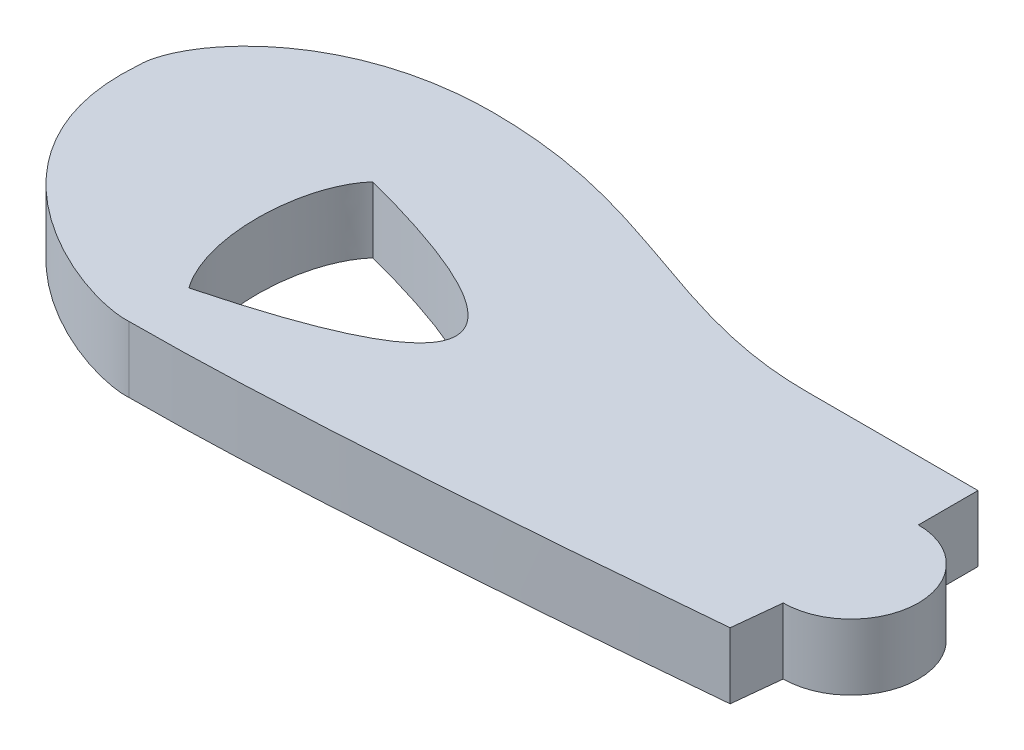
SolidWorks part; units mm, degrees
ref_plane "Front Plane" through (0, 0, 0) normal (0, 0, 1) x (1, 0, 0)
ref_plane "Top Plane" through (0, 0, 0) normal (0, 1, 0) x (1, 0, 0)
ref_plane "Right Plane" through (0, 0, 0) normal (1, 0, 0) x (0, 0, -1)
sketch "Sketch1" plane through (0, 0, 0) normal (0, 1, 0) x (1, 0, 0)
  line L0 (0, 0) -> (29.8, 0) construction
  line L1 (0, 0) -> (0, 24.3) construction
  line L2 (0, 0) -> (0, -22.5) construction
  line L3 (0, 0) -> (-86.5, 0) construction
  line L4 (-26, 0) -> (-26, 24.3) construction
  line L5 (-86.5, 0) -> (-86.5, 37.2) construction
  line L6 (-86.5, 11.6) -> (-124.6, 11.6) construction
  line L7 (-86.5, 0) -> (-86.5, -27.9) construction
  dimension "D1" = 29.8
  dimension "D2" = 24.3
  dimension "D3" = 22.5
  dimension "D4" = 26
  dimension "D5" = 86.5
  dimension "D6" = 27.9
  dimension "D7" = 37.2
  dimension "D8" = 11.6
  dimension "D9" = 38.1
sketch "Sketch2" plane through (0, 0, 0) normal (0, 1, 0) x (1, 0, 0)
  line L0 (-26, 24.3) -> (0, 24.3)
  line L1 (-124.6, 0.1449) -> (-124.6, 23.0551) construction
  line L2 (-106.5667, 37.2) -> (-66.4333, 37.2) construction
  line L3 (-42.2984, 24.3) -> (-9.7006, 24.3) construction
  line L4 (-107.4998, 37.2) -> (-65.4572, 37.2) construction
  line L5 (-64.2941, -27.9) -> (-108.7059, -27.9) construction
  line L6 (29.8, -11.2792) -> (29.8, 11.2792) construction
  line L7 (29.8, -14.0147) -> (29.8, 14.0918) construction
  spline S0 degree 3 poles (-26, 24.3) (-46.3736, 24.3) (-60.2234, 37.2) (-86.5, 37.2) knots 0 0 0 0 1 1 1 1
  spline S1 degree 3 poles (-86.5, 37.2) (-111.5833, 37.2) (-124.6, 21.1459) (-124.6, 11.6) knots 0 0 0 0 1 1 1 1
  spline S2 degree 3 poles (0, 24.3) (20.6838, 24.3847) (29.8, 14.099) (29.8, 0) knots 0 0 0 0 1 1 1 1
  spline S3 degree 3 poles (29.8, 0) (29.8, -15.9034) (12.7938, -19.6737) (0, -22.5) knots 0 0 0 0 1 1 1 1
  spline S4 degree 2 poles (-86.5, -27.9) (-58.7426, -27.9) (0, -22.5) knots 0 0 0 1 1 1
  spline S5 degree 3 poles (-124.6, 11.6) (-126.6455, -15.9296) (-96.1692, -28.4589) (-86.5, -27.9) knots 0 0 0 0 1 1 1 1
  point P0 (0, 24.3)
  point P2 (29.8, 0)
  point P4 (0, -22.5)
  point P6 (-26, 24.3)
  point P8 (-86.5, 37.2)
  point P10 (-124.6, 11.6)
  point P12 (-86.5, -27.9)
extrude "Boss-Extrude1" add sketch "Sketch2" along normal blind 10
sketch "Sketch5" plane through (0, 10, 0) normal (0, 1, 0) x (1, 0, 0)
  line L2 (0, 19.3) -> (-26, 19.3)
  line L3 (0, 19.3) -> (-26, 19.3)
  line L4 (-133.1401, 55.1699) -> (57.5258, 55.1699)
  line L5 (-133.1401, 55.1699) -> (-133.1401, -43.745)
  line L6 (-133.1401, -43.745) -> (57.5258, -43.745)
  line L7 (57.5258, 55.1699) -> (57.5258, -43.745)
  spline S10 degree 3 poles (794.3178, 2896.6346) (236.5633, 295.2684) (75.1344, 4.3942) (-36.2999, 20.219) (-38.8232, 20.7499) (-43.8284, 22.0533) (-46.3131, 22.8262) (-51.2444, 24.4704) (-53.694, 25.3411) (-58.6071, 27.0407) (-61.0707, 27.8688) (-64.8063, 28.9893) (-66.0595, 29.343) (-68.5722, 29.9962) (-69.8324, 30.2958) (-73.6263, 31.1023) (-76.1734, 31.5152) (-394.4154, 65.5197) (-1008.6606, -1988.9699) (-1423.0021, -2645.3199) knots -5.207716 -5.207716 -5.207716 -5.207716 0.125 0.125 0.25 0.25 0.375 0.375 0.5 0.5 0.625 0.625 0.6875 0.6875 0.75 0.75 0.875 0.875 16.247306 16.247306 16.247306 16.247306 only from (-26, 19.3) to (-86.5, 32.2)
  spline S11 degree 3 poles (-155.0275, 3009.7498) (283.9644, -579.3508) (39.2092, 61.7589) (-97.8181, 30.8894) (-98.6695, 30.6698) (-100.363, 30.1729) (-101.2079, 29.8946) (-103.7072, 28.973) (-105.3145, 28.249) (-108.4025, 26.5648) (-109.8852, 25.604) (-112.6954, 23.4124) (-113.9894, 22.2093) (-115.7364, 20.2177) (-116.2861, 19.5225) (-117.3076, 18.0567) (-117.7719, 17.2971) (-118.3806, 16.1123) (-118.5688, 15.7095) (-118.9104, 14.8853) (-119.0639, 14.463) (-119.321, 13.6124) (-119.4258, 13.1825) (-119.5345, 12.528) (-119.5626, 12.3083) (-119.5889, 11.9755) (-119.595, 11.8641) (-119.8529, 2.1663) (-91.4737, -13.0524) (-3067.996, 562.8701) knots -9.69525 -9.69525 -9.69525 -9.69525 0.25 0.25 0.3125 0.3125 0.375 0.375 0.5 0.5 0.625 0.625 0.75 0.75 0.8125 0.8125 0.875 0.875 0.90625 0.90625 0.9375 0.9375 0.96875 0.96875 0.984375 0.984375 0.992188 0.992188 1.660503 1.660503 1.660503 1.660503 only from (-86.5, 32.2) to (-119.6, 11.4145)
  spline S12 degree 3 poles (-3114.144, -159.344) (-75.3215, 65.211) (-118.2824, 36.1888) (-119.6695, 10.3135) (-119.7026, 9.4894) (-119.7017, 8.668) (-119.6533, 7.0291) (-119.5587, 5.9417) (-119.3168, 4.3187) (-119.2195, 3.7791) (-118.9903, 2.7027) (-118.8578, 2.164) (-118.4114, 0.5683) (-118.0496, -0.4661) (-117.2048, -2.4791) (-116.7219, -3.4578) (-115.911, -4.8862) (-115.6263, -5.3557) (-115.0287, -6.2817) (-114.7151, -6.739) (-113.0981, -8.9672) (-111.6366, -10.5868) (-109.2434, -12.8211) (-108.4118, -13.5331) (-107.1168, -14.5549) (-106.6765, -14.8883) (-105.787, -15.5353) (-105.3374, -15.8493) (-103.0661, -17.3743) (-101.1758, -18.4523) (-98.2376, -19.8702) (-97.2408, -20.3092) (-95.21, -21.1148) (-94.1746, -21.4822) (-92.0643, -22.1268) (-91.001, -22.402) (-89.3879, -22.7093) (-88.8471, -22.7942) (-88.0288, -22.8795) (-87.7547, -22.9009) (-87.3409, -22.9165) (-87.2025, -22.919) (-75.8543, -22.7912) (-57.6729, 17.6935) (-565.1077, -2984.244) knots -1.438804 -1.438804 -1.438804 -1.438804 0.015625 0.015625 0.03125 0.0625 0.0625 0.125 0.125 0.15625 0.15625 0.1875 0.1875 0.25 0.25 0.3125 0.3125 0.34375 0.34375 0.375 0.375 0.5 0.5 0.5625 0.5625 0.59375 0.59375 0.625 0.625 0.75 0.75 0.8125 0.8125 0.875 0.875 0.9375 0.9375 0.96875 0.96875 0.984375 0.984375 0.992187 0.992187 1.621629 1.621629 1.621629 1.621629 only from (-119.6, 11.4145) to (-86.6438, -22.9)
  spline S13 degree 3 poles (-743.0619, 2883.7324) (-404.1471, 44.7095) (-237.6226, -27.3739) (-72.2929, -22.6309) (-68.7098, -22.4892) (-57.9653, -21.9864) (-50.8087, -21.5494) (-36.5025, -20.5633) (-29.353, -20.0121) (442.1069, 18.8609) (896.2577, 220.25) (1524.6058, -2374.3013) knots -5.513822 -5.513822 -5.513822 -5.513822 0.125 0.125 0.25 0.25 0.5 0.5 0.75 0.75 16.991268 16.991268 16.991268 16.991268 only from (-86.6438, -22.9) to (-0.7711, -17.5498)
  spline S14 degree 3 poles (684.9632, -2932.2413) (-188.4077, 55.2091) (-72.0811, -37.5503) (8.73, -15.2186) (10.0645, -14.8145) (12.6997, -13.9014) (14.0008, -13.3934) (15.9119, -12.5052) (16.5421, -12.1879) (17.7844, -11.497) (18.3919, -11.1257) (19.5594, -10.3246) (20.1212, -9.8941) (20.9205, -9.1892) (21.1807, -8.9434) (21.6785, -8.4347) (21.9161, -8.1719) (22.5926, -7.3563) (22.9947, -6.7761) (23.5131, -5.8423) (23.6718, -5.5198) (23.9536, -4.8681) (24.0777, -4.5373) (24.4029, -3.5305) (24.5567, -2.8403) (31.3062, 45.0348) (-209.6675, 121.1409) (2725.17, -1306.3496) knots -7.13592 -7.13592 -7.13592 -7.13592 0.25 0.25 0.375 0.375 0.5 0.5 0.5625 0.5625 0.625 0.625 0.6875 0.6875 0.71875 0.71875 0.75 0.75 0.8125 0.8125 0.84375 0.84375 0.875 0.875 0.9375 0.9375 5.110249 5.110249 5.110249 5.110249 only from (-0.7711, -17.5498) to (24.8, 0)
  spline S15 degree 3 poles (3003.4514, 307.3213) (-329.5265, -207.9997) (38.0399, -68.0338) (24.2703, 5.1555) (24.0952, 5.8744) (23.7648, 6.9407) (23.6433, 7.2941) (23.3755, 7.9966) (23.2292, 8.3451) (22.7584, 9.3658) (22.3999, 10.019) (21.5892, 11.2682) (21.1362, 11.865) (19.6347, 13.56) (18.4892, 14.5137) (16.9097, 15.5257) (16.5854, 15.7195) (15.9298, 16.0859) (15.5982, 16.2589) (14.5926, 16.7499) (13.9081, 17.0401) (12.5153, 17.5579) (11.807, 17.7854) (10.3698, 18.1863) (9.6387, 18.36) (7.4366, 18.806) (5.959, 19.0045) (-85.4866, 26.721) (-201.9485, -238.1682) (23.3888, 3011.2925) knots -6.115667 -6.115667 -6.115667 -6.115667 0.125 0.125 0.1875 0.1875 0.21875 0.21875 0.25 0.25 0.3125 0.3125 0.375 0.375 0.5 0.5 0.53125 0.53125 0.5625 0.5625 0.625 0.625 0.6875 0.6875 0.75 0.75 0.875 0.875 8.448739 8.448739 8.448739 8.448739 only from (24.8, 0) to (0, 19.3)
  spline S16 degree 3 poles (-26, 19.3) (-28.6144, 19.3) (-31.1955, 19.4941) (-36.2999, 20.219) (-38.8232, 20.7499) (-43.8284, 22.0533) (-46.3131, 22.8262) (-51.2444, 24.4704) (-53.694, 25.3411) (-58.6071, 27.0407) (-61.0707, 27.8688) (-64.8063, 28.9893) (-66.0595, 29.343) (-68.5722, 29.9962) (-69.8324, 30.2958) (-73.6263, 31.1023) (-76.1734, 31.5152) (-81.3072, 32.0638) (-83.8939, 32.2) (-86.5, 32.2) knots 0 0 0 0 0.125 0.125 0.25 0.25 0.375 0.375 0.5 0.5 0.625 0.625 0.6875 0.6875 0.75 0.75 0.875 0.875 1 1 1 1
  spline S17 degree 3 poles (-86.5, 32.2) (-90.0477, 32.2) (-93.5393, 31.8534) (-97.8181, 30.8894) (-98.6695, 30.6698) (-100.363, 30.1729) (-101.2079, 29.8946) (-103.7072, 28.973) (-105.3145, 28.249) (-108.4025, 26.5648) (-109.8852, 25.604) (-112.6954, 23.4124) (-113.9894, 22.2093) (-115.7364, 20.2177) (-116.2861, 19.5225) (-117.3076, 18.0567) (-117.7719, 17.2971) (-118.3806, 16.1123) (-118.5688, 15.7095) (-118.9104, 14.8853) (-119.0639, 14.463) (-119.321, 13.6124) (-119.4258, 13.1825) (-119.5345, 12.528) (-119.5626, 12.3083) (-119.5889, 11.9755) (-119.595, 11.8641) (-119.6009, 11.64) (-119.6, 11.5271) (-119.6, 11.4145) knots 0 0 0 0 0.25 0.25 0.3125 0.3125 0.375 0.375 0.5 0.5 0.625 0.625 0.75 0.75 0.8125 0.8125 0.875 0.875 0.90625 0.90625 0.9375 0.9375 0.96875 0.96875 0.984375 0.984375 0.992188 0.992188 1 1 1 1
  spline S18 degree 3 poles (-119.6, 11.4145) (-119.6205, 11.139) (-119.64, 10.8636) (-119.6695, 10.3135) (-119.7026, 9.4894) (-119.7017, 8.668) (-119.6533, 7.0291) (-119.5587, 5.9417) (-119.3168, 4.3187) (-119.2195, 3.7791) (-118.9903, 2.7027) (-118.8578, 2.164) (-118.4114, 0.5683) (-118.0496, -0.4661) (-117.2048, -2.4791) (-116.7219, -3.4578) (-115.911, -4.8862) (-115.6263, -5.3557) (-115.0287, -6.2817) (-114.7151, -6.739) (-113.0981, -8.9672) (-111.6366, -10.5868) (-109.2434, -12.8211) (-108.4118, -13.5331) (-107.1168, -14.5549) (-106.6765, -14.8883) (-105.787, -15.5353) (-105.3374, -15.8493) (-103.0661, -17.3743) (-101.1758, -18.4523) (-98.2376, -19.8702) (-97.2408, -20.3092) (-95.21, -21.1148) (-94.1746, -21.4822) (-92.0643, -22.1268) (-91.001, -22.402) (-89.3879, -22.7093) (-88.8471, -22.7942) (-88.0288, -22.8795) (-87.7547, -22.9009) (-87.3409, -22.9165) (-87.2025, -22.919) (-86.9242, -22.9159) (-86.784, -22.9081) (-86.6438, -22.9) knots 0 0 0 0 0.015625 0.015625 0.03125 0.0625 0.0625 0.125 0.125 0.15625 0.15625 0.1875 0.1875 0.25 0.25 0.3125 0.3125 0.34375 0.34375 0.375 0.375 0.5 0.5 0.5625 0.5625 0.59375 0.59375 0.625 0.625 0.75 0.75 0.8125 0.8125 0.875 0.875 0.9375 0.9375 0.96875 0.96875 0.984375 0.984375 0.992187 0.992187 1 1 1 1
  spline S19 degree 3 poles (-86.6438, -22.9) (-83.0517, -22.9018) (-79.4639, -22.8367) (-72.2929, -22.6309) (-68.7098, -22.4892) (-57.9653, -21.9864) (-50.8087, -21.5494) (-36.5025, -20.5633) (-29.353, -20.0121) (-15.0588, -18.8335) (-7.9141, -18.2056) (-0.7711, -17.5498) knots 0 0 0 0 0.125 0.125 0.25 0.25 0.5 0.5 0.75 0.75 1 1 1 1
  spline S20 degree 3 poles (-0.7711, -17.5498) (1.9633, -16.9454) (4.6953, -16.3336) (8.73, -15.2186) (10.0645, -14.8145) (12.6997, -13.9014) (14.0008, -13.3934) (15.9119, -12.5052) (16.5421, -12.1879) (17.7844, -11.497) (18.3919, -11.1257) (19.5594, -10.3246) (20.1212, -9.8941) (20.9205, -9.1892) (21.1807, -8.9434) (21.6785, -8.4347) (21.9161, -8.1719) (22.5926, -7.3563) (22.9947, -6.7761) (23.5131, -5.8423) (23.6718, -5.5198) (23.9536, -4.8681) (24.0777, -4.5373) (24.4029, -3.5305) (24.5567, -2.8403) (24.756, -1.4273) (24.8, -0.7143) (24.8, 0) knots 0 0 0 0 0.25 0.25 0.375 0.375 0.5 0.5 0.5625 0.5625 0.625 0.625 0.6875 0.6875 0.71875 0.71875 0.75 0.75 0.8125 0.8125 0.84375 0.84375 0.875 0.875 0.9375 0.9375 1 1 1 1
  spline S21 degree 3 poles (24.8, 0) (24.8, 1.4998) (24.6799, 2.9783) (24.2703, 5.1555) (24.0952, 5.8744) (23.7648, 6.9407) (23.6433, 7.2941) (23.3755, 7.9966) (23.2292, 8.3451) (22.7584, 9.3658) (22.3999, 10.019) (21.5892, 11.2682) (21.1362, 11.865) (19.6347, 13.56) (18.4892, 14.5137) (16.9097, 15.5257) (16.5854, 15.7195) (15.9298, 16.0859) (15.5982, 16.2589) (14.5926, 16.7499) (13.9081, 17.0401) (12.5153, 17.5579) (11.807, 17.7854) (10.3698, 18.1863) (9.6387, 18.36) (7.4366, 18.806) (5.959, 19.0045) (2.9895, 19.2551) (1.4975, 19.3061) (0, 19.3) knots 0 0 0 0 0.125 0.125 0.1875 0.1875 0.21875 0.21875 0.25 0.25 0.3125 0.3125 0.375 0.375 0.5 0.5 0.53125 0.53125 0.5625 0.5625 0.625 0.625 0.6875 0.6875 0.75 0.75 0.875 0.875 1 1 1 1
  dimension "D1" = 5
extrude "Cut-Extrude2" cut sketch "Sketch5" against normal through all
sketch "Sketch3" plane through (0, 10, 0) normal (0, 1, 0) x (1, 0, 0)
  line L0 (0, 0) -> (-59.9237, 0) construction
  line L1 (0, 0) -> (-86.5, 0) construction
  line L2 (-59.9237, 0) -> (-86.5, 13.95) construction
  line L3 (-86.5, 0) -> (-86.5, 37.2) construction
  line L4 (-86.5, 13.95) -> (-86.5, -13.95) construction
  line L5 (-86.5, 0) -> (-86.5, -27.9) construction
  line L6 (-86.5, -13.95) -> (-59.9237, 0) construction
  line L7 (0, 0) -> (0, 24.3) construction
  line L12 (0, 0) -> (0, -22.5) construction
  line L13 (0, 19.3) -> (0, 10.2587)
  line L14 (0, -10.2587) -> (-0.7711, -17.5498)
  arc A0 (0, 10.2587) -> (0, -10.2587) centre (0, 0) cw
  spline S0 degree 3 poles (-86.5, -13.95) (-91.9618, -6.4228) (-91.7175, 8.0405) (-86.5, 13.95) knots 0 0 0 0 1 1 1 1
  spline S1 degree 2 poles (-86.5, 13.95) (-33.3474, 0) (-86.5, -13.95) knots 0 0 0 1 1 1
  spline S4 degree 3 poles (2014.7792, 157.4755) (-251.7771, -177.4141) (36.5089, -59.896) (24.2703, 5.1555) (24.0952, 5.8744) (23.7648, 6.9407) (23.6433, 7.2941) (23.3755, 7.9966) (23.2292, 8.3451) (22.7584, 9.3658) (22.3999, 10.019) (21.5892, 11.2682) (21.1362, 11.865) (19.6347, 13.56) (18.4892, 14.5137) (16.9097, 15.5257) (16.5854, 15.7195) (15.9298, 16.0859) (15.5982, 16.2589) (14.5926, 16.7499) (13.9081, 17.0401) (12.5153, 17.5579) (11.807, 17.7854) (10.3698, 18.1863) (9.6387, 18.36) (7.4366, 18.806) (5.959, 19.0045) (-75.0154, 25.8374) (-175.1957, -180.1948) (-41.9858, 2013.4713) knots -5.414826 -5.414826 -5.414826 -5.414826 0.125 0.125 0.1875 0.1875 0.21875 0.21875 0.25 0.25 0.3125 0.3125 0.375 0.375 0.5 0.5 0.53125 0.53125 0.5625 0.5625 0.625 0.625 0.6875 0.6875 0.75 0.75 0.875 0.875 7.567171 7.567171 7.567171 7.567171 only from (24.8, 0) to (0, 19.3) construction
  spline S5 degree 3 poles (407.8796, -1971.4254) (-160.6006, 34.3029) (-62.3962, -34.8739) (8.73, -15.2186) (10.0645, -14.8145) (12.6997, -13.9014) (14.0008, -13.3934) (15.9119, -12.5052) (16.5421, -12.1879) (17.7844, -11.497) (18.3919, -11.1257) (19.5594, -10.3246) (20.1212, -9.8941) (20.9205, -9.1892) (21.1807, -8.9434) (21.6785, -8.4347) (21.9161, -8.1719) (22.5926, -7.3563) (22.9947, -6.7761) (23.5131, -5.8423) (23.6718, -5.5198) (23.9536, -4.8681) (24.0777, -4.5373) (24.4029, -3.5305) (24.5567, -2.8403) (30.5346, 39.562) (-157.0824, 103.8698) (1826.5255, -867.8005) knots -6.235759 -6.235759 -6.235759 -6.235759 0.25 0.25 0.375 0.375 0.5 0.5 0.5625 0.5625 0.625 0.625 0.6875 0.6875 0.71875 0.71875 0.75 0.75 0.8125 0.8125 0.84375 0.84375 0.875 0.875 0.9375 0.9375 4.626099 4.626099 4.626099 4.626099 only from (-0.7711, -17.5498) to (24.8, 0) construction
  spline S6 degree 3 poles (24.8, 0) (24.8, 1.4998) (24.6799, 2.9783) (24.2703, 5.1555) (24.0952, 5.8744) (23.7648, 6.9407) (23.6433, 7.2941) (23.3755, 7.9966) (23.2292, 8.3451) (22.7584, 9.3658) (22.3999, 10.019) (21.5892, 11.2682) (21.1362, 11.865) (19.6347, 13.56) (18.4892, 14.5137) (16.9097, 15.5257) (16.5854, 15.7195) (15.9298, 16.0859) (15.5982, 16.2589) (14.5926, 16.7499) (13.9081, 17.0401) (12.5153, 17.5579) (11.807, 17.7854) (10.3698, 18.1863) (9.6387, 18.36) (7.4366, 18.806) (5.959, 19.0045) (2.9895, 19.2551) (1.4975, 19.3061) (0, 19.3) knots 0 0 0 0 0.125 0.125 0.1875 0.1875 0.21875 0.21875 0.25 0.25 0.3125 0.3125 0.375 0.375 0.5 0.5 0.53125 0.53125 0.5625 0.5625 0.625 0.625 0.6875 0.6875 0.75 0.75 0.875 0.875 1 1 1 1
  spline S7 degree 3 poles (-0.7711, -17.5498) (1.9633, -16.9454) (4.6953, -16.3336) (8.73, -15.2186) (10.0645, -14.8145) (12.6997, -13.9014) (14.0008, -13.3934) (15.9119, -12.5052) (16.5421, -12.1879) (17.7844, -11.497) (18.3919, -11.1257) (19.5594, -10.3246) (20.1212, -9.8941) (20.9205, -9.1892) (21.1807, -8.9434) (21.6785, -8.4347) (21.9161, -8.1719) (22.5926, -7.3563) (22.9947, -6.7761) (23.5131, -5.8423) (23.6718, -5.5198) (23.9536, -4.8681) (24.0777, -4.5373) (24.4029, -3.5305) (24.5567, -2.8403) (24.756, -1.4273) (24.8, -0.7143) (24.8, 0) knots 0 0 0 0 0.25 0.25 0.375 0.375 0.5 0.5 0.5625 0.5625 0.625 0.625 0.6875 0.6875 0.71875 0.71875 0.75 0.75 0.8125 0.8125 0.84375 0.84375 0.875 0.875 0.9375 0.9375 1 1 1 1
extrude "Cut-Extrude1" cut sketch "Sketch3" against normal through all
